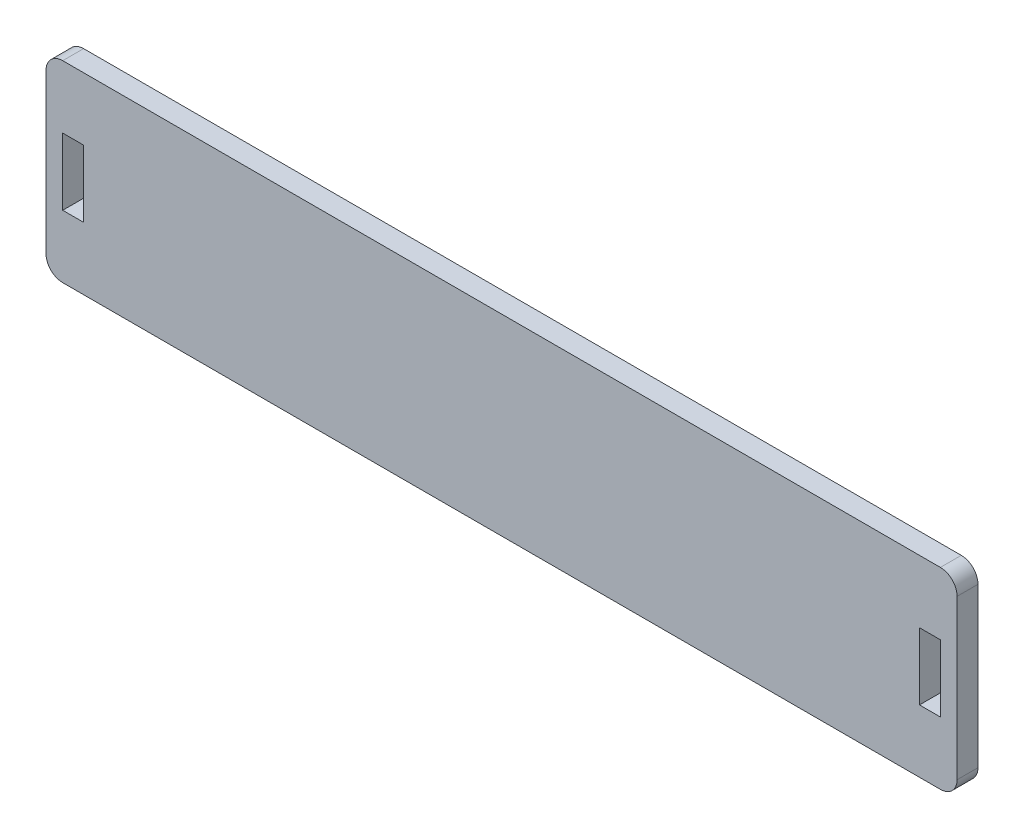
SolidWorks part; units mm, degrees
material "Beech"
ref_plane "Front" through (0, 0, 0) normal (0, 0, 1) x (1, 0, 0)
ref_plane "Top" through (0, 0, 0) normal (0, 1, 0) x (1, 0, 0)
ref_plane "Right" through (0, 0, 0) normal (1, 0, 0) x (0, 0, -1)
sketch "Sketch1" plane through (0, 0, 0) normal (0, 0, 1) x (1, 0, 0)
  line L0 (0, -5.6139) -> (0, 7.3412) construction
  line L1 (-54.5, -11.5) -> (54.5, -11.5)
  line L2 (-54.5, -11.5) -> (-54.5, 11.5)
  line L3 (-54.5, 11.5) -> (54.5, 11.5)
  line L4 (54.5, -11.5) -> (54.5, 11.5)
  line L5 (-54.5, -11.5) -> (54.5, 11.5) construction
  line L6 (-54.5, 11.5) -> (54.5, -11.5) construction
  line L7 (50, -4) -> (52.5, -4)
  line L8 (50, -4) -> (50, 4)
  line L9 (50, 4) -> (52.5, 4)
  line L10 (52.5, -4) -> (52.5, 4)
  line L11 (50, -4) -> (52.5, 4) construction
  line L12 (50, 4) -> (52.5, -4) construction
  line L13 (-50, 4) -> (-52.5, 4)
  line L14 (-52.5, -4) -> (-52.5, 4)
  line L15 (-50, -4) -> (-52.5, -4)
  line L16 (-50, -4) -> (-50, 4)
  point P0 (0, 0)
  point P6 (51.25, 0)
  point P13 (54.5, 0)
  dimension "D1" = 109
  dimension "D2" = 2
  dimension "D3" = 2.5
  dimension "D4" = 8
  dimension "D5" = 23
extrude "Boss-Extrude1" add sketch "Sketch1" along normal blind 2.5
fillet "Fillet1" radius 2 4 edges at (54.5, -11.5, 1.25) (54.5, 11.5, 1.25) (-54.5, -11.5, 1.25) (-54.5, 11.5, 1.25)
sketch "Sketch2" plane through (0, 0, 0) normal (0, 0, -1) x (-1, 0, 0)
  line L0 (-12.5, 1.5) -> (12.5, 1.5) construction
  line L1 (12.5, -2.5) -> (-12.5, -2.5) construction
  line L2 (-52.5, 11.5) -> (52.5, 11.5) construction
  text T0 "OPPOSITE\r\n" font "Century Gothic" height 3
  text T1 "Made In Egypt" font "Century Gothic" height 1.75
  point P4 (0, 0)
  point P7 (0, 1.5)
  point P8 (0, 11.5)
  dimension "D1" = 4
  dimension "D2" = 10
  dimension "D3" = 25
extrude "Cut-Extrude1" cut sketch "Sketch2" against normal blind 1
